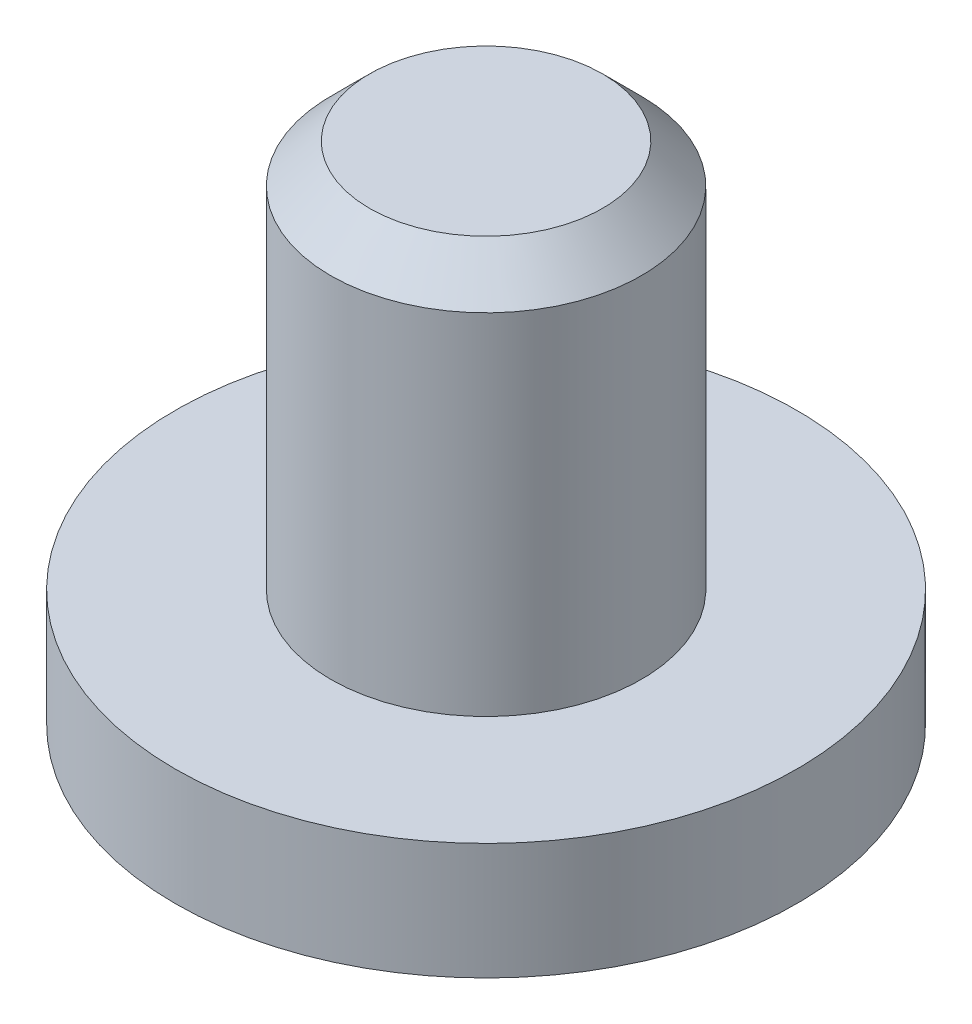
SolidWorks part; units mm, degrees
ref_plane "前视基准面" through (0, 0, 0) normal (0, 0, 1) x (1, 0, 0)
ref_plane "上视基准面" through (0, 0, 0) normal (0, 1, 0) x (1, 0, 0)
ref_plane "右视基准面" through (0, 0, 0) normal (1, 0, 0) x (0, 0, -1)
sketch "草图2" plane through (0, 0, 0) normal (0, 0, 1) x (1, 0, 0)
  line L0 (0, 0) -> (4, 0)
  line L1 (4, 0) -> (4, 1.5)
  line L2 (4, 1.5) -> (2, 1.5)
  line L3 (2, 1.5) -> (2, 6.5)
  line L4 (2, 6.5) -> (0, 6.5)
  line L5 (0, 6.5) -> (0, 0)
  dimension "D1" = 1.5
  dimension "D2" = 2
  dimension "D3" = 4
  dimension "D4" = 5
revolve "旋转1" add sketch "草图2" angle 360 about L5
chamfer "倒角1" distance 0.5 angle 45 1 edges at (0, 6.5, 2)
